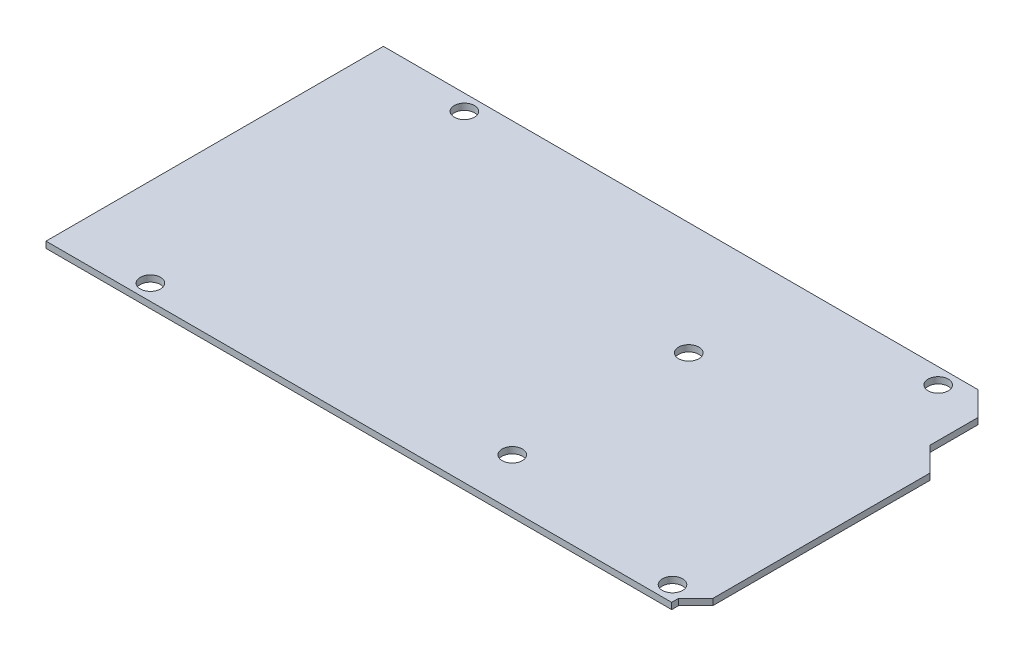
SolidWorks part; units mm, degrees
ref_plane "Front Plane" through (0, 0, 0) normal (0, 0, 1) x (1, 0, 0)
ref_plane "Top Plane" through (0, 0, 0) normal (0, 1, 0) x (1, 0, 0)
ref_plane "Right Plane" through (0, 0, 0) normal (1, 0, 0) x (0, 0, -1)
sketch "Sketch1" plane through (0, 0, 0) normal (0, 1, 0) x (1, 0, 0)
  line L0 (9.8247, -25.0838) -> (483.869, -25.0838) construction
  line L1 (101.61, 38.09) -> (97.8, 41.9)
  line L6 (0, 0) -> (101.61, 0)
  line L7 (0, 0) -> (0, 53.33)
  line L8 (0, 53.33) -> (101.61, 53.33)
  line L9 (101.61, 0) -> (101.61, 53.33)
  line L10 (101.61, 53.33) -> (97.8, 53.33)
  line L11 (101.61, 53.33) -> (101.61, 38.09)
  line L12 (101.61, 38.09) -> (97.8, 38.09)
  line L13 (97.8, 53.33) -> (97.8, 38.09)
  line L14 (97.8, 49.52) -> (93.99, 53.33)
  line L15 (101.61, 3.81) -> (97.8, 0)
  line L16 (98.9, 1.1) -> (98.9, 0)
  circle A0 centre (14, 2.5) radius 1.6
  circle A1 centre (15.3, 50.83) radius 1.6
  circle A2 centre (66.1, 35.5) radius 1.6
  circle A3 centre (66.1, 7.6) radius 1.6
  circle A4 centre (90.2, 50.83) radius 1.6
  circle A5 centre (96.53, 2.5) radius 1.6
  dimension "D10" = 3.2
  dimension "D1" = 101.61
  dimension "D2" = 53.33
  dimension "D3" = 15.24
  dimension "D4" = 3.81
  dimension "D5" = 3.81
  dimension "D6" = 3.81
  dimension "D7" = 3.81
  dimension "D8" = 3.81
  dimension "D9" = 3.81
  dimension "D11" = 14
  dimension "D12" = 15.3
  dimension "D13" = 66.1
  dimension "D14" = 90.2
  dimension "D15" = 96.53
  dimension "D16" = 2.5
  dimension "D17" = 2.5
  dimension "D18" = 7.6
  dimension "D19" = 27.9
  dimension "D20" = 1.1
extrude "Arduino Template" add sketch "Sketch1" along normal blind 1 contours L15 L9 L12 L13 L14 L8 L7 L6 A5 A4 A3 A2 A1 A0 | L16 L15 L6 | L1 L13 L12
